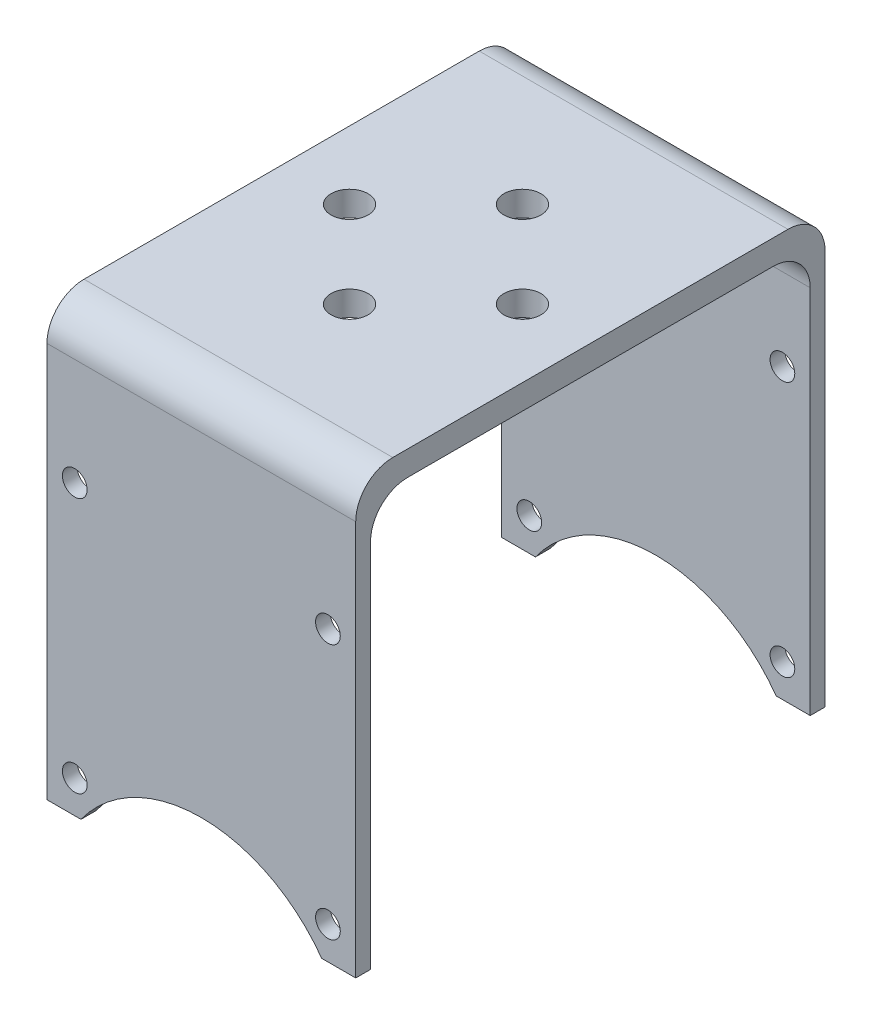
SolidWorks part; units mm, degrees
ref_plane "前视基准面" through (0, 0, 0) normal (0, 0, 1) x (1, 0, 0)
ref_plane "上视基准面" through (0, 0, 0) normal (0, 1, 0) x (1, 0, 0)
ref_plane "右视基准面" through (0, 0, 0) normal (1, 0, 0) x (0, 0, -1)
sketch "草图1" plane through (0, 0, 0) normal (0, 1, 0) x (1, 0, 0)
  line L0 (12.5, -10) -> (12.5, -19)
  line L1 (-20.5, 10) -> (-12.5, 10)
  line L2 (-20.5, 10) -> (-20.5, -10)
  line L3 (-20.5, -10) -> (-12.5, -10)
  line L4 (20.5, 10) -> (20.5, -10)
  line L5 (-20.5, 10) -> (20.5, -10) construction
  line L6 (-20.5, -10) -> (20.5, 10) construction
  line L7 (-12.5, 19) -> (12.5, 19)
  line L8 (-12.5, 19) -> (-12.5, 10)
  line L9 (-12.5, -19) -> (12.5, -19)
  line L10 (12.5, 19) -> (12.5, 10)
  line L11 (-12.5, 19) -> (12.5, -19) construction
  line L12 (-12.5, -19) -> (12.5, 19) construction
  line L13 (12.5, -10) -> (20.5, -10)
  line L14 (-12.5, -10) -> (-12.5, -19)
  line L15 (12.5, 10) -> (20.5, 10)
  point P0 (0, 0)
  point P6 (0, 0)
  dimension "D1" = 41
  dimension "D2" = 20
  dimension "D3" = 25
  dimension "D4" = 38
extrude "凸台-拉伸1" add sketch "草图1" along normal blind 2
sketch "草图4" plane through (0, 0, 0) normal (0, -1, 0) x (1, 0, 0)
  line L0 (12.5, 19) -> (12.5, 10) construction
  line L1 (-12.5, 19) -> (12.5, 19)
  line L2 (-12.5, 19) -> (-12.5, 17.8)
  line L3 (-12.5, 17.8) -> (12.5, 17.8)
  line L4 (12.5, 19) -> (12.5, 17.8)
  line L5 (-12.5, -19) -> (-12.5, -10) construction
  line L6 (12.5, -19) -> (-12.5, -19)
  line L7 (12.5, -19) -> (12.5, -17.8)
  line L8 (12.5, -17.8) -> (-12.5, -17.8)
  line L9 (-12.5, -19) -> (-12.5, -17.8)
  dimension "D1" = 1.2
  dimension "D2" = 1.2
extrude "凸台-拉伸3" add sketch "草图4" along normal blind 40
fillet "圆角2" radius 3 4 edges at (0, 0, -17.8) (0, 2, -19) (0, 2, 19) (0, 0, 17.8)
sketch "草图7" plane through (0, 0, 19) normal (0, 0, 1) x (1, 0, 0)
  line L0 (0, -46.3202) -> (0, 14.2704) construction
  line L1 (-25.5668, 0) -> (26.1896, 0) construction
  line L2 (-12.5, -33) -> (-9.7468, -33)
  line L3 (-10.25, -30.35) -> (10.25, -30.35) construction
  line L4 (-10.25, -30.35) -> (-10.25, -9.65) construction
  line L5 (-10.25, -9.65) -> (10.25, -9.65) construction
  line L6 (10.25, -30.35) -> (10.25, -9.65) construction
  line L7 (-10.25, -30.35) -> (10.25, -9.65) construction
  line L8 (-10.25, -9.65) -> (10.25, -30.35) construction
  line L9 (-12.5, -1) -> (-12.5, -40) construction
  line L10 (12.5, -1) -> (12.5, -40) construction
  line L11 (12.5, -33) -> (12.5, -40)
  line L12 (12.5, -40) -> (-12.5, -40)
  line L13 (-12.5, -40) -> (-12.5, -33)
  line L14 (9.7468, -33) -> (12.5, -33)
  circle A0 centre (-10.25, -30.35) radius 1
  circle A1 centre (-10.25, -9.65) radius 1
  circle A2 centre (10.25, -9.65) radius 1
  circle A3 centre (10.25, -30.35) radius 1
  arc A4 (-9.7468, -33) -> (9.7468, -33) centre (0, -40) cw
  point P5 (0, -20)
  dimension "D4" = 2
  dimension "D5" = 2
  dimension "D6" = 2
  dimension "D7" = 2
  dimension "D10" = 12
  dimension "D1" = 20.5
  dimension "D2" = 20.7
  dimension "D3" = 20
  dimension "D8" = 33
  dimension "D9" = 40
extrude "切除-拉伸3" cut sketch "草图7" against normal through all
sketch "草图8" plane through (0, 2, 0) normal (0, 1, 0) x (1, 0, 0)
  line L1 (12.5, 19) -> (-12.5, 19)
  line L2 (12.5, 19) -> (12.5, -19)
  line L3 (12.5, -19) -> (-12.5, -19)
  line L4 (-12.5, 19) -> (-12.5, -19)
  line L5 (12.5, 19) -> (-12.5, -19) construction
  line L6 (12.5, -19) -> (-12.5, 19) construction
  point P0 (0, 0)
extrude "切除-拉伸4" cut sketch "草图8" against normal blind 10 flip side to cut
sketch "草图9" plane through (0, 2, 0) normal (0, 1, 0) x (1, 0, 0)
  line L0 (0, 21.3706) -> (0, -23.2272) construction
  line L2 (15.0305, 0) -> (-15.8996, 0) construction
  circle A0 centre (0, 0) radius 7 construction
  circle A1 centre (0, -7) radius 1.5
  circle A2 centre (-7, 0) radius 1.5
  circle A3 centre (0, 7) radius 1.5
  circle A4 centre (7, 0) radius 1.5
  point P18 (0, 0)
  dimension "D1" = 14
  dimension "D2" = 3
  dimension "D3" = 4
extrude "切除-拉伸5" cut sketch "草图9" against normal blind 10
